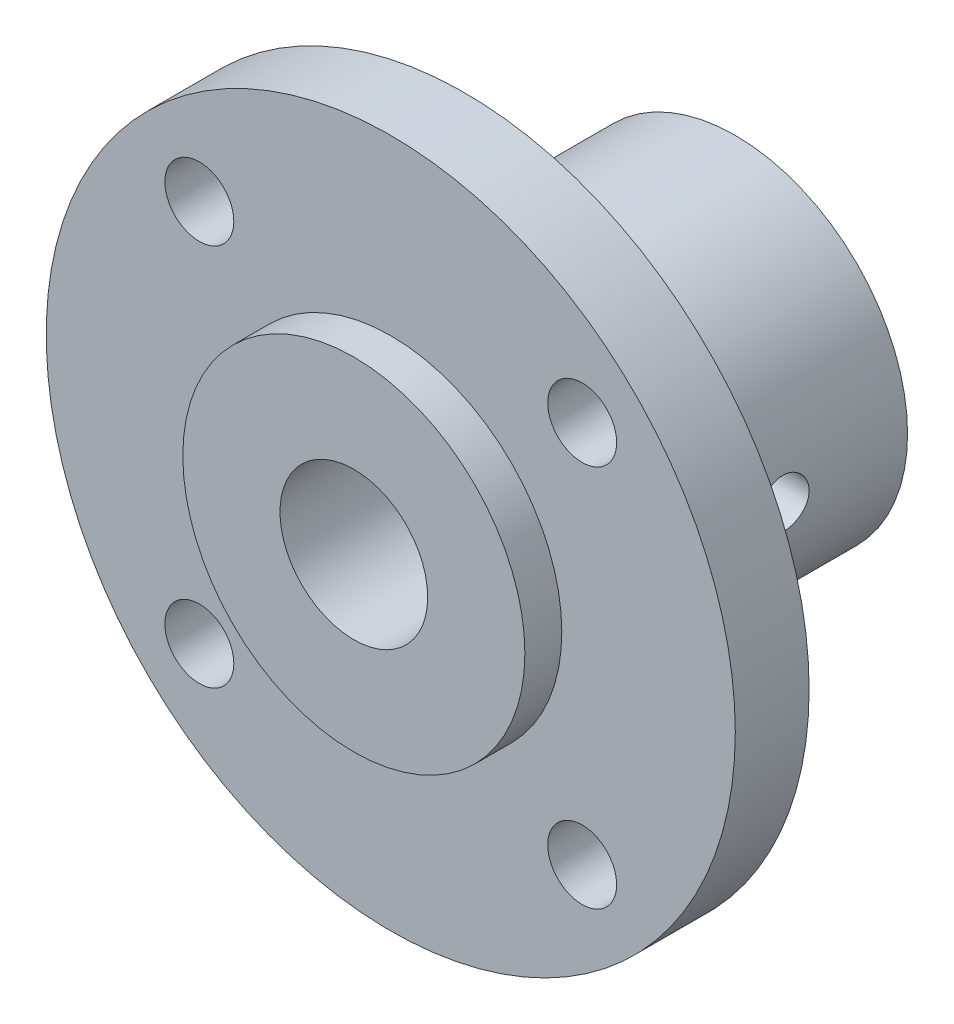
SolidWorks part; units mm, degrees
material "7075-T6 (SN)"
ref_plane "Front Plane" through (0, 0, 0) normal (0, 0, 1) x (1, 0, 0)
ref_plane "Top Plane" through (0, 0, 0) normal (0, 1, 0) x (1, 0, 0)
ref_plane "Right Plane" through (0, 0, 0) normal (1, 0, 0) x (0, 0, -1)
sketch "Sketch1" plane through (0, 0, 0) normal (0, 0, 1) x (1, 0, 0)
  circle A0 centre (0, 0) radius 14
extrude "Boss-Extrude1" add sketch "Sketch1" along normal blind 3
sketch "Sketch2" plane through (0, 0, 3) normal (0, 0, 1) x (1, 0, 0)
  circle A0 centre (0, 0) radius 6.95
extrude "Boss-Extrude2" add sketch "Sketch2" along normal blind 1.5
sketch "Sketch3" plane through (0, 0, 4.5) normal (0, 0, 1) x (1, 0, 0)
  circle A0 centre (0, 0) radius 3
extrude "Cut-Extrude1" cut sketch "Sketch3" against normal through all
sketch "Sketch4" plane through (0, 0, 0) normal (0, 0, 1) x (1, 0, 0)
  circle A0 centre (0, 0) radius 7
  circle A1 centre (0, 0) radius 3
extrude "Shaft_Hub_Collar_L11" add sketch "Sketch4" along normal blind 11 from offset 11
sketch "Sketch5" plane through (0, 0, 0) normal (0, 0, -1) x (-1, 0, 0)
  circle A0 centre (-7.7782, 7.7782) radius 1.4
  circle A1 centre (7.7782, 7.7782) radius 1.4
  circle A2 centre (7.7782, -7.7782) radius 1.4
  circle A3 centre (-7.7782, -7.7782) radius 1.4
extrude "Flange_Four_D2p8_PCD22" cut sketch "Sketch5" against normal blind 3.01
sketch "Sketch6" plane through (0, 0, 0) normal (1, 0, 0) x (0, 0, -1)
  circle A0 centre (6, 0) radius 1
extrude "DIN1481_D2_Cross_Pin_Hole" cut sketch "Sketch6" against normal through all and the other way through all
